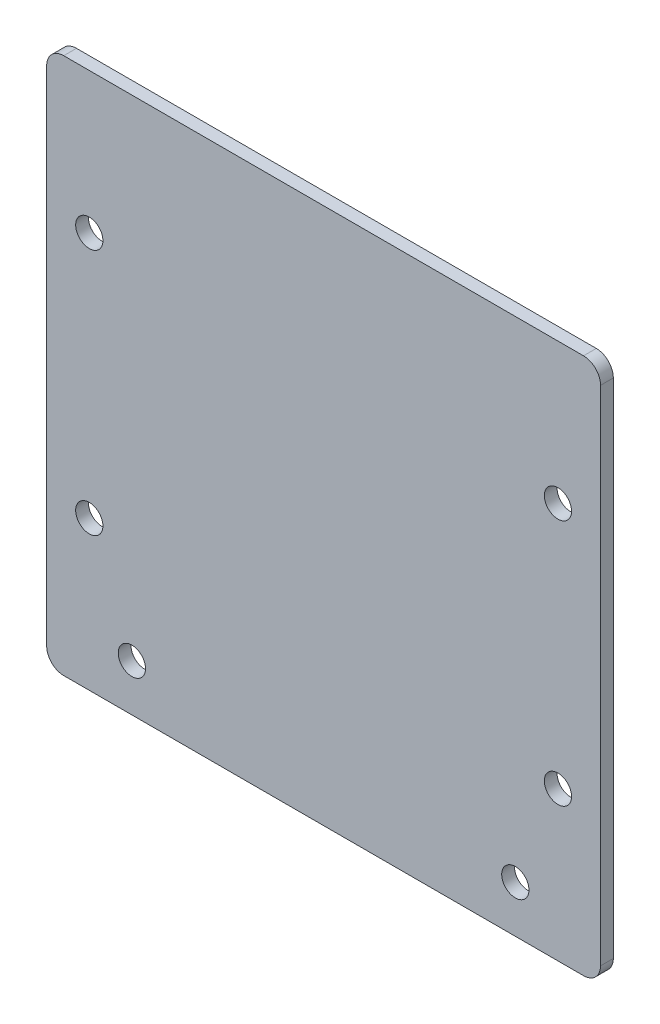
SolidWorks part; units mm, degrees
ref_plane "前视基准面" through (0, 0, 0) normal (0, 0, 1) x (1, 0, 0)
ref_plane "上视基准面" through (0, 0, 0) normal (0, 1, 0) x (1, 0, 0)
ref_plane "右视基准面" through (0, 0, 0) normal (1, 0, 0) x (0, 0, -1)
sketch "草图2" plane through (0, 0, 0) normal (0, 0, 1) x (1, 0, 0)
  line L0 (-27.5, -14) -> (-22.5, -26) construction
  line L1 (-27.5, 15) -> (27.5, 15) construction
  line L2 (-27.5, 15) -> (-27.5, -14) construction
  line L3 (-27.5, -14) -> (27.5, -14) construction
  line L4 (27.5, 15) -> (27.5, -14) construction
  line L6 (-32.5, -31.5) -> (32.5, -31.5)
  line L7 (27.5, -14) -> (22.5, -26) construction
  line L8 (-32.5, -31.5) -> (-32.5, 31.5)
  line L9 (-32.5, 31.5) -> (32.5, 31.5)
  line L10 (32.5, -31.5) -> (32.5, 31.5)
  line L12 (-32.5, -31.5) -> (32.5, 31.5) construction
  line L13 (-32.5, 31.5) -> (32.5, -31.5) construction
  line L14 (-22.5, -26) -> (22.5, -26) construction
  circle A0 centre (-27.5, -14) radius 1.6
  circle A1 centre (-27.5, 15) radius 1.6
  circle A2 centre (27.5, 15) radius 1.6
  circle A3 centre (27.5, -14) radius 1.6
  circle A4 centre (22.5, -26) radius 1.6
  circle A5 centre (-22.5, -26) radius 1.6
  point P4 (0, 15)
  point P5 (0, 0)
  dimension "D3" = 3.2
  dimension "D1" = 29
  dimension "D2" = 12
  dimension "D4" = 45
  dimension "D5" = 65
  dimension "D6" = 55
  dimension "D7" = 63
  dimension "D8" = 5.5
extrude "凸台-拉伸1" add sketch "草图2" along normal blind 1.5
fillet "圆角1" radius 2 4 edges at (-32.5, 31.5, 0.75) (32.5, -31.5, 0.75) (-32.5, -31.5, 0.75) (32.5, 31.5, 0.75)
